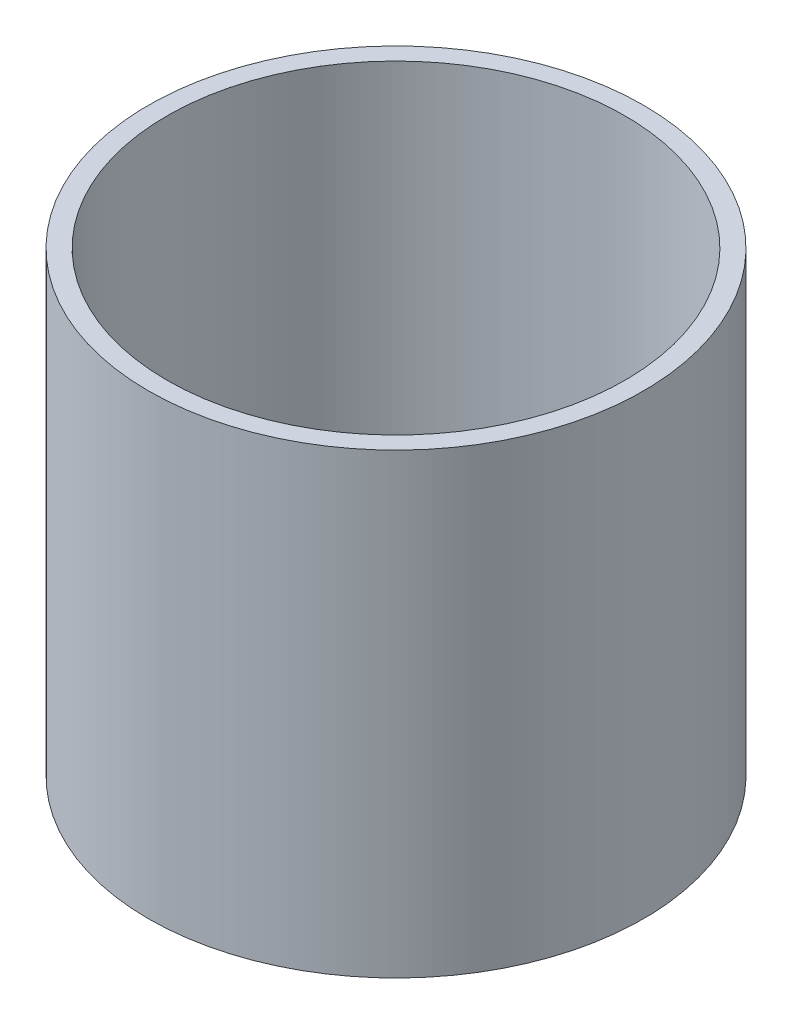
SolidWorks part; units mm, degrees
ref_plane "Front Plane" through (0, 0, 0) normal (0, 0, 1) x (1, 0, 0)
ref_plane "Top Plane" through (0, 0, 0) normal (0, 1, 0) x (1, 0, 0)
ref_plane "Right Plane" through (0, 0, 0) normal (1, 0, 0) x (0, 0, -1)
sketch "Sketch1" plane through (0, 0, 0) normal (0, 1, 0) x (1, 0, 0)
  circle A0 centre (0, 0) radius 27.5
  circle A1 centre (0, 0) radius 25.45
  dimension "D1" = 55
  dimension "D2" = 50.9
extrude "Boss-Extrude1" add sketch "Sketch1" along normal blind 50.8
